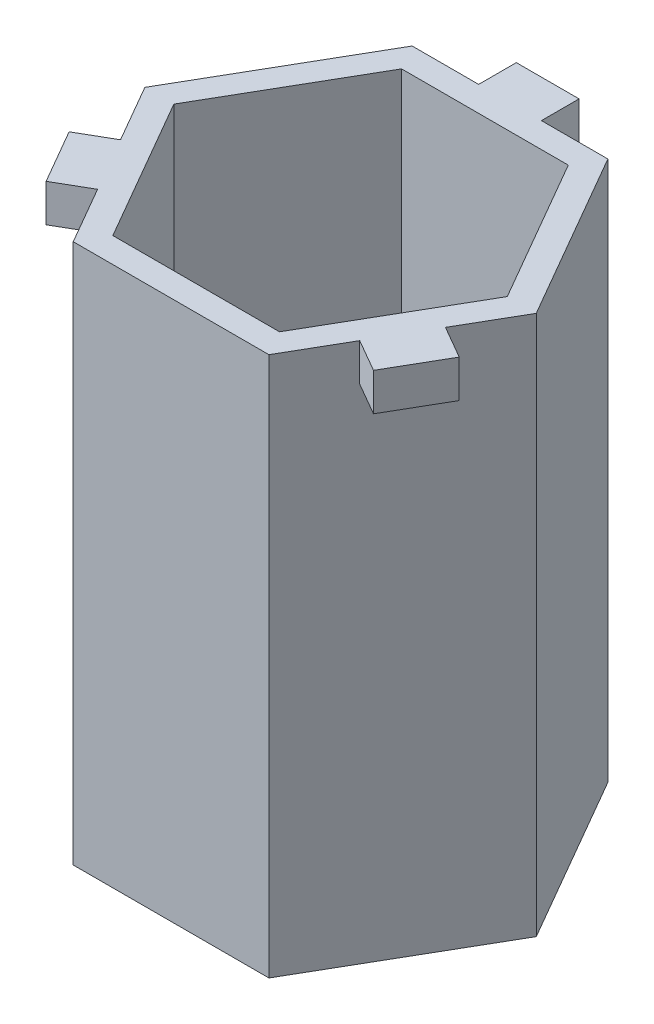
SolidWorks part; units mm, degrees
ref_plane "Front Plane" through (0, 0, 0) normal (0, 0, 1) x (1, 0, 0)
ref_plane "Top Plane" through (0, 0, 0) normal (0, 1, 0) x (1, 0, 0)
ref_plane "Right Plane" through (0, 0, 0) normal (1, 0, 0) x (0, 0, -1)
sketch "Sketch1" plane through (0, 0, 0) normal (0, 1, 0) x (1, 0, 0)
  line L1 (15.5885, 0) -> (7.7942, 13.5)
  line L2 (7.7942, 13.5) -> (-7.7942, 13.5)
  line L3 (-7.7942, 13.5) -> (-15.5885, 0)
  line L4 (-15.5885, 0) -> (-7.7942, -13.5)
  line L5 (-7.7942, -13.5) -> (7.7942, -13.5)
  line L6 (7.7942, -13.5) -> (15.5885, 0)
  circle A0 centre (0, 0) radius 13.5 construction
  circle A1 centre (0, 0) radius 10.7
  dimension "D2" = 21.4
  dimension "D1" = 27
extrude "Boss-Extrude1" add sketch "Sketch1" along normal blind 43
sketch "Sketch2" plane through (0, 43, 0) normal (0, 1, 0) x (1, 0, 0)
  line L1 (13.2791, 0) -> (6.6395, 11.5)
  line L2 (6.6395, 11.5) -> (-6.6395, 11.5)
  line L3 (-6.6395, 11.5) -> (-13.2791, 0)
  line L4 (-13.2791, 0) -> (-6.6395, -11.5)
  line L5 (-6.6395, -11.5) -> (6.6395, -11.5)
  line L6 (6.6395, -11.5) -> (13.2791, 0)
  circle A0 centre (0, 0) radius 11.5 construction
  circle A1 centre (0, 0) radius 11.5 construction
  dimension "D1" = 23
extrude "Cut-Extrude1" cut sketch "Sketch2" along direction (0, 1, 0) on the side against the normal offset from surface (40 mm away) 3
sketch "Sketch3" plane through (0, 43, 0) normal (0, 1, 0) x (1, 0, 0)
  line L0 (0, 0) -> (0, 13.5) construction
  line L1 (7.7942, 13.5) -> (-7.7942, 13.5) construction
  line L2 (15.5394, -6.0849) -> (12.9413, -4.5849)
  line L3 (-2.5, 16.5) -> (2.5, 16.5)
  line L4 (-2.5, 16.5) -> (-2.5, 13.5)
  line L5 (-2.5, 13.5) -> (2.5, 13.5)
  line L6 (2.5, 16.5) -> (2.5, 13.5)
  line L7 (15.5394, -6.0849) -> (13.0394, -10.4151)
  line L8 (13.0394, -10.4151) -> (10.4413, -8.9151)
  line L9 (12.9413, -4.5849) -> (10.4413, -8.9151)
  line L10 (-13.0394, -10.4151) -> (-10.4413, -8.9151)
  line L11 (-13.0394, -10.4151) -> (-15.5394, -6.0849)
  line L12 (-15.5394, -6.0849) -> (-12.9413, -4.5849)
  line L13 (-10.4413, -8.9151) -> (-12.9413, -4.5849)
  point P19 (0, 0)
  dimension "D1" = 5
  dimension "D2" = 3
  dimension "D3" = 3
extrude "Boss-Extrude2" add sketch "Sketch3" against normal blind 3
